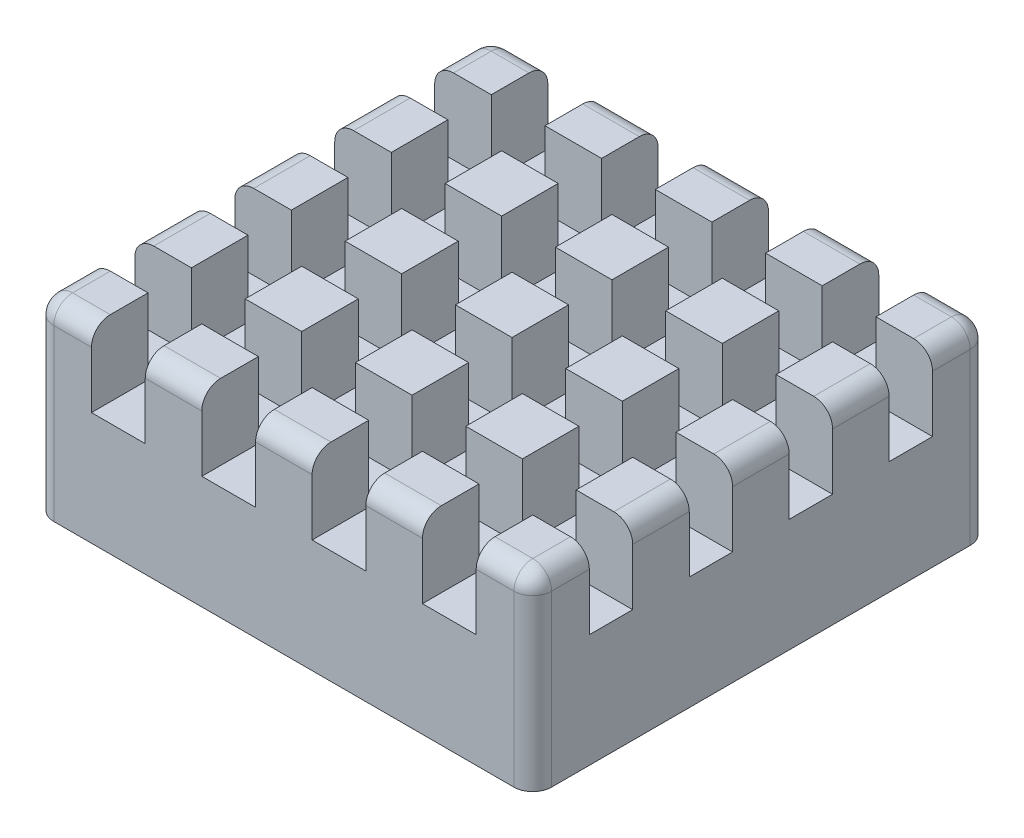
SolidWorks part; units mm, degrees
material "Copper"
ref_plane "Front Plane" through (0, 0, 0) normal (0, 0, 1) x (1, 0, 0)
ref_plane "Top Plane" through (0, 0, 0) normal (0, 1, 0) x (1, 0, 0)
ref_plane "Right Plane" through (0, 0, 0) normal (1, 0, 0) x (0, 0, -1)
sketch "Sketch1" plane through (0, 0, 0) normal (0, 1, 0) x (1, 0, 0)
  line L1 (0, 0) -> (13.2, 0)
  line L2 (0, 0) -> (0, 12.1)
  line L3 (0, 12.1) -> (13.2, 12.1)
  line L4 (13.2, 0) -> (13.2, 12.1)
  dimension "D1" = 13.2
  dimension "D2" = 12.1
extrude "Boss-Extrude1" add sketch "Sketch1" against normal blind 3
sketch "Sketch2" plane through (0, 0, 0) normal (0, 1, 0) x (1, 0, 0)
  line L0 (2.925, 12.1) -> (2.925, 10.6)
  line L1 (0, 12.1) -> (1.5, 12.1)
  line L2 (0, 12.1) -> (0, 10.6)
  line L3 (0, 10.6) -> (1.5, 10.6)
  line L4 (1.5, 12.1) -> (1.5, 10.6)
  line L5 (2.925, 12.1) -> (4.425, 12.1)
  line L6 (4.425, 12.1) -> (4.425, 10.6)
  line L7 (2.925, 10.6) -> (4.425, 10.6)
  line L8 (5.85, 12.1) -> (5.85, 10.6)
  line L9 (5.85, 12.1) -> (7.35, 12.1)
  line L10 (7.35, 12.1) -> (7.35, 10.6)
  line L11 (5.85, 10.6) -> (7.35, 10.6)
  line L12 (8.775, 12.1) -> (8.775, 10.6)
  line L13 (8.775, 12.1) -> (10.275, 12.1)
  line L14 (10.275, 12.1) -> (10.275, 10.6)
  line L15 (8.775, 10.6) -> (10.275, 10.6)
  line L16 (11.7, 12.1) -> (11.7, 10.6)
  line L17 (11.7, 12.1) -> (13.2, 12.1)
  line L18 (13.2, 12.1) -> (13.2, 10.6)
  line L19 (11.7, 10.6) -> (13.2, 10.6)
  line L20 (2.925, 9.45) -> (2.925, 7.95)
  line L21 (2.925, 9.45) -> (4.425, 9.45)
  line L22 (4.425, 9.45) -> (4.425, 7.95)
  line L23 (2.925, 7.95) -> (4.425, 7.95)
  line L24 (5.85, 9.45) -> (5.85, 7.95)
  line L25 (5.85, 9.45) -> (7.35, 9.45)
  line L26 (7.35, 9.45) -> (7.35, 7.95)
  line L27 (5.85, 7.95) -> (7.35, 7.95)
  line L28 (8.775, 9.45) -> (8.775, 7.95)
  line L29 (8.775, 9.45) -> (10.275, 9.45)
  line L30 (10.275, 9.45) -> (10.275, 7.95)
  line L31 (8.775, 7.95) -> (10.275, 7.95)
  line L32 (11.7, 9.45) -> (11.7, 7.95)
  line L33 (11.7, 9.45) -> (13.2, 9.45)
  line L34 (13.2, 9.45) -> (13.2, 7.95)
  line L35 (11.7, 7.95) -> (13.2, 7.95)
  line L36 (2.925, 6.8) -> (2.925, 5.3)
  line L37 (2.925, 6.8) -> (4.425, 6.8)
  line L38 (4.425, 6.8) -> (4.425, 5.3)
  line L39 (2.925, 5.3) -> (4.425, 5.3)
  line L40 (5.85, 6.8) -> (5.85, 5.3)
  line L41 (5.85, 6.8) -> (7.35, 6.8)
  line L42 (7.35, 6.8) -> (7.35, 5.3)
  line L43 (5.85, 5.3) -> (7.35, 5.3)
  line L44 (8.775, 6.8) -> (8.775, 5.3)
  line L45 (8.775, 6.8) -> (10.275, 6.8)
  line L46 (10.275, 6.8) -> (10.275, 5.3)
  line L47 (8.775, 5.3) -> (10.275, 5.3)
  line L48 (11.7, 6.8) -> (11.7, 5.3)
  line L49 (11.7, 6.8) -> (13.2, 6.8)
  line L50 (13.2, 6.8) -> (13.2, 5.3)
  line L51 (11.7, 5.3) -> (13.2, 5.3)
  line L52 (2.925, 4.15) -> (2.925, 2.65)
  line L53 (2.925, 4.15) -> (4.425, 4.15)
  line L54 (4.425, 4.15) -> (4.425, 2.65)
  line L55 (2.925, 2.65) -> (4.425, 2.65)
  line L56 (5.85, 4.15) -> (5.85, 2.65)
  line L57 (5.85, 4.15) -> (7.35, 4.15)
  line L58 (7.35, 4.15) -> (7.35, 2.65)
  line L59 (5.85, 2.65) -> (7.35, 2.65)
  line L60 (8.775, 4.15) -> (8.775, 2.65)
  line L61 (8.775, 4.15) -> (10.275, 4.15)
  line L62 (10.275, 4.15) -> (10.275, 2.65)
  line L63 (8.775, 2.65) -> (10.275, 2.65)
  line L64 (11.7, 4.15) -> (11.7, 2.65)
  line L65 (11.7, 4.15) -> (13.2, 4.15)
  line L66 (13.2, 4.15) -> (13.2, 2.65)
  line L67 (11.7, 2.65) -> (13.2, 2.65)
  line L68 (2.925, 1.5) -> (2.925, 0)
  line L69 (2.925, 1.5) -> (4.425, 1.5)
  line L70 (4.425, 1.5) -> (4.425, 0)
  line L71 (2.925, 0) -> (4.425, 0)
  line L72 (5.85, 1.5) -> (5.85, 0)
  line L73 (5.85, 1.5) -> (7.35, 1.5)
  line L74 (7.35, 1.5) -> (7.35, 0)
  line L75 (5.85, 0) -> (7.35, 0)
  line L76 (8.775, 1.5) -> (8.775, 0)
  line L77 (8.775, 1.5) -> (10.275, 1.5)
  line L78 (10.275, 1.5) -> (10.275, 0)
  line L79 (8.775, 0) -> (10.275, 0)
  line L80 (11.7, 1.5) -> (11.7, 0)
  line L81 (11.7, 1.5) -> (13.2, 1.5)
  line L82 (13.2, 1.5) -> (13.2, 0)
  line L83 (11.7, 0) -> (13.2, 0)
  line L84 (0, 9.45) -> (0, 7.95)
  line L85 (0, 9.45) -> (1.5, 9.45)
  line L86 (1.5, 9.45) -> (1.5, 7.95)
  line L87 (0, 7.95) -> (1.5, 7.95)
  line L88 (0, 6.8) -> (0, 5.3)
  line L89 (0, 6.8) -> (1.5, 6.8)
  line L90 (1.5, 6.8) -> (1.5, 5.3)
  line L91 (0, 5.3) -> (1.5, 5.3)
  line L92 (0, 4.15) -> (0, 2.65)
  line L93 (0, 4.15) -> (1.5, 4.15)
  line L94 (1.5, 4.15) -> (1.5, 2.65)
  line L95 (0, 2.65) -> (1.5, 2.65)
  line L96 (0, 1.5) -> (0, 0)
  line L97 (0, 1.5) -> (1.5, 1.5)
  line L98 (1.5, 1.5) -> (1.5, 0)
  line L99 (0, 0) -> (1.5, 0)
  point P5 (13.2, 0)
  point P6 (13.2, 12.1)
  dimension "D1" = 1.5
  dimension "D2" = 5
  dimension "D3" = 5
extrude "Boss-Extrude2" add sketch "Sketch2" along normal blind 2
fillet "Fillet1" radius 0.5 24 edges at (13.2, 2, -8.7) (13.2, 2, -6.05) (13.2, 2, -3.4) (9.525, 2, 0) (6.6, 2, 0) (3.675, 2, 0) (0, 2, -3.4) (0, 2, -6.05) (0, 2, -8.7) (3.675, 2, -12.1) (6.6, 2, -12.1) (9.525, 2, -12.1) (0.75, 2, -12.1) (0, 2, -11.35) (0, 2, -0.75) (0.75, 2, 0) (12.45, 2, 0) (13.2, 2, -0.75) (13.2, 2, -11.35) (12.45, 2, -12.1) (0, -0.5, -12.1) (13.2, -0.5, -12.1) (0, -0.5, 0) (13.2, -0.5, 0)
